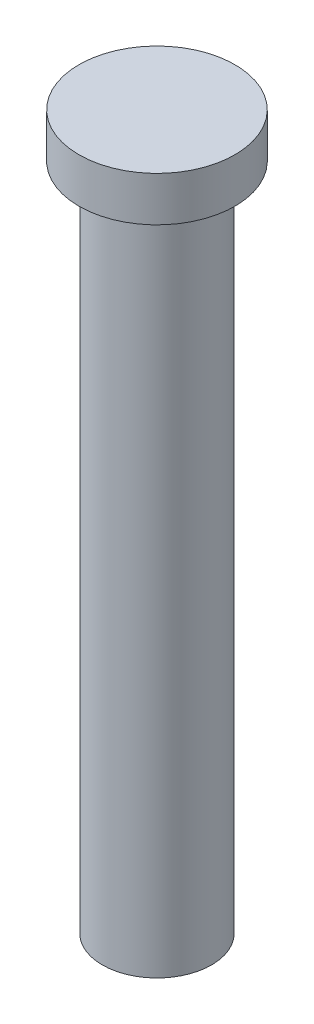
SolidWorks part; units mm, degrees
ref_plane "Front Plane" through (0, 0, 0) normal (0, 0, 1) x (1, 0, 0)
ref_plane "Top Plane" through (0, 0, 0) normal (0, 1, 0) x (1, 0, 0)
ref_plane "Right Plane" through (0, 0, 0) normal (1, 0, 0) x (0, 0, -1)
sketch "Sketch1" plane through (0, 0, 0) normal (0, 1, 0) x (1, 0, 0)
  circle A0 centre (0, 0) radius 2.45
  dimension "D1" = 4.9
extrude "Boss-Extrude1" add sketch "Sketch1" along normal blind 30
sketch "Sketch2" plane through (0, 30, 0) normal (0, 1, 0) x (1, 0, 0)
  circle A0 centre (0, 0) radius 3.5
  dimension "D1" = 7
extrude "Boss-Extrude2" add sketch "Sketch2" along normal blind 2
